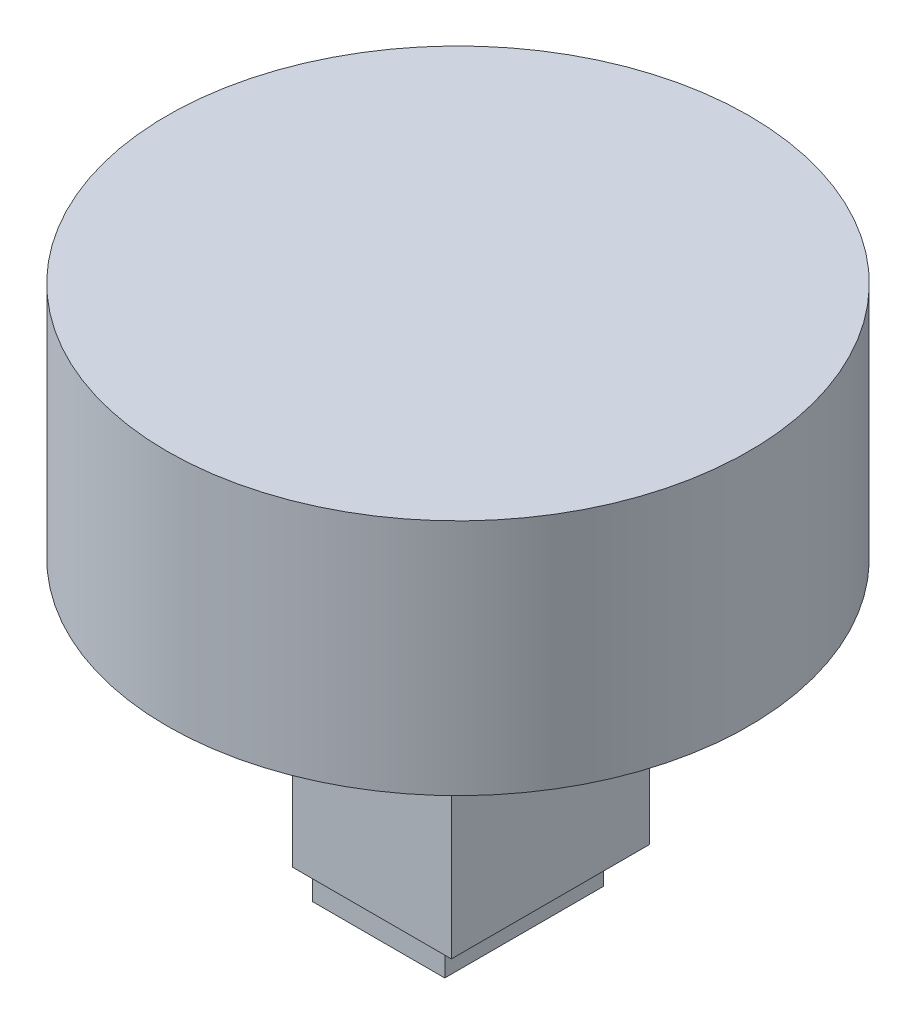
SolidWorks part; units mm, degrees
ref_plane "前视基准面" through (0, 0, 0) normal (0, 0, 1) x (1, 0, 0)
ref_plane "上视基准面" through (0, 0, 0) normal (0, 1, 0) x (1, 0, 0)
ref_plane "右视基准面" through (0, 0, 0) normal (1, 0, 0) x (0, 0, -1)
sketch "草图1" plane through (0, 0, 0) normal (0, 1, 0) x (1, 0, 0)
  circle A0 centre (0, 0) radius 22
  dimension "D1" = 44
extrude "凸台-拉伸1" add sketch "草图1" along normal blind 18
sketch "草图2" plane through (0, 0, 0) normal (0, -1, 0) x (1, 0, 0)
  line L1 (-5, 6) -> (5, 6)
  line L2 (-5, 6) -> (-5, -6)
  line L3 (-5, -6) -> (5, -6)
  line L4 (5, 6) -> (5, -6)
  line L5 (-5, 6) -> (5, -6) construction
  line L6 (-5, -6) -> (5, 6) construction
  point P0 (0, 0)
  dimension "D1" = 10
  dimension "D2" = 12
extrude "凸台-拉伸2" add sketch "草图2" along normal blind 22
sketch "草图3" plane through (5, 0, 0) normal (1, 0, 0) x (0, 0, -1)
  line L0 (0, 0) -> (0, -24.4654) construction
  line L1 (6, 0) -> (-6, 0) construction
  line L2 (6, -22) -> (-6, -22) construction
  line L3 (-7.5, -19) -> (7.5, -19)
  line L4 (-7.5, -19) -> (-7.5, -7)
  line L5 (-7.5, -7) -> (7.5, -7)
  line L6 (7.5, -19) -> (7.5, -7)
  line L7 (-7.5, -19) -> (7.5, -7) construction
  line L8 (-7.5, -7) -> (7.5, -19) construction
  point P4 (0, -13)
  point P9 (0, -14.9923)
  dimension "D1" = 15
  dimension "D2" = 12
  dimension "D3" = 3
extrude "凸台-拉伸3" add sketch "草图3" along normal blind 2 and the other way up to surface other way up to face at (-5, -11, 0)
